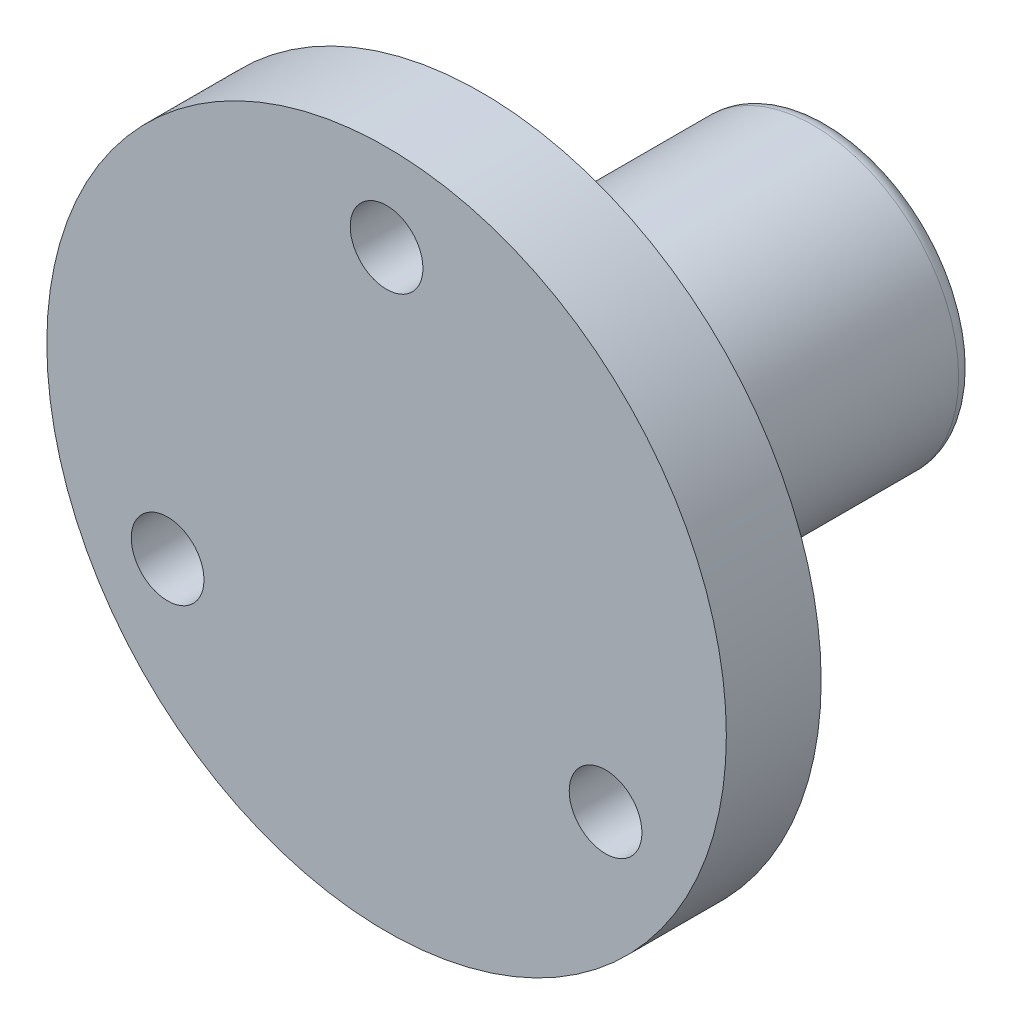
SolidWorks part; units mm, degrees
ref_plane "Front Plane" through (0, 0, 0) normal (0, 0, 1) x (1, 0, 0)
ref_plane "Top Plane" through (0, 0, 0) normal (0, 1, 0) x (1, 0, 0)
ref_plane "Right Plane" through (0, 0, 0) normal (1, 0, 0) x (0, 0, -1)
sketch "Sketch1" plane through (0, 0, 0) normal (0, 0, 1) x (1, 0, 0)
  line L1 (18.0877, -4.5031) -> (21.7623, -4.5031)
  line L2 (19.925, -4.5031) -> (19.925, -7) construction
  line L3 (18.0877, -4.5031) -> (19.925, -7) construction
  arc A0 (18.0877, -4.5031) -> (21.7623, -4.5031) centre (19.925, -7) ccw
  circle A1 centre (19.925, -7) radius 4.6
  dimension "D1" = 1.5
  dimension "D2" = 36.347
extrude "Boss-Extrude1" add sketch "Sketch1" against normal blind 11
sketch "Sketch2" plane through (0, 0, 0) normal (0, 0, 1) x (1, 0, 0)
  line L0 (19.925, -7) -> (12.9968, -11) construction
  line L1 (19.925, -7) -> (19.925, 1) construction
  line L2 (19.925, -7) -> (26.8532, -11) construction
  circle A0 centre (19.925, -7) radius 10.75
  circle A3 centre (19.925, -7) radius 8 construction
  circle A4 centre (19.925, 1) radius 1.15
  circle A6 centre (12.9968, -11) radius 1.15
  circle A7 centre (26.8532, -11) radius 1.15
  dimension "D1" = 21.5
  dimension "D6" = 16
  dimension "D7" = 2.3
  dimension "D2" = 120
  dimension "D3" = 120
extrude "Boss-Extrude2" add sketch "Sketch2" along normal blind 3
sketch "Sketch3" plane through (0, 0, 0) normal (0, 0, -1) x (-1, 0, 0)
  line L0 (-19.925, -4.5031) -> (-19.925, -7) construction
  line L1 (-25.5542, -8.75) -> (-28.1522, -8.75)
  line L2 (-28.1522, -8.75) -> (-29.4513, -11)
  line L3 (-29.4513, -11) -> (-28.1522, -13.25)
  line L4 (-28.1522, -13.25) -> (-25.5542, -13.25)
  line L5 (-25.5542, -13.25) -> (-24.2551, -11)
  line L6 (-24.2551, -11) -> (-25.5542, -8.75)
  line L7 (-22.5231, 1) -> (-21.224, -1.25)
  line L8 (-21.224, -1.25) -> (-18.626, -1.25)
  line L9 (-18.626, -1.25) -> (-17.3269, 1)
  line L10 (-17.3269, 1) -> (-18.626, 3.25)
  line L11 (-18.626, 3.25) -> (-21.224, 3.25)
  line L12 (-21.224, 3.25) -> (-22.5231, 1)
  line L13 (-14.2958, -8.75) -> (-15.5949, -11)
  line L14 (-15.5949, -11) -> (-14.2958, -13.25)
  line L15 (-14.2958, -13.25) -> (-11.6978, -13.25)
  line L16 (-11.6978, -13.25) -> (-10.3987, -11)
  line L17 (-10.3987, -11) -> (-11.6978, -8.75)
  line L18 (-11.6978, -8.75) -> (-14.2958, -8.75)
  line L19 (-21.7623, -4.5031) -> (-18.0877, -4.5031) construction
  circle A0 centre (-26.8532, -11) radius 2.25 construction
  circle A1 centre (-19.925, 1) radius 2.25 construction
  circle A2 centre (-12.9968, -11) radius 2.25 construction
  point P19 (-22.2255, 0.7977)
  dimension "D1" = 4.5
  dimension "D2" = 30
  dimension "D3" = 30
extrude "Cut-Extrude1" cut sketch "Sketch3" against normal blind 1
chamfer "Chamfer1" distance 1 angle 45 1 edges at (24.525, -7, 0)
fillet "Fillet1" radius 0.5 1 edges at (24.525, -7, -11)
